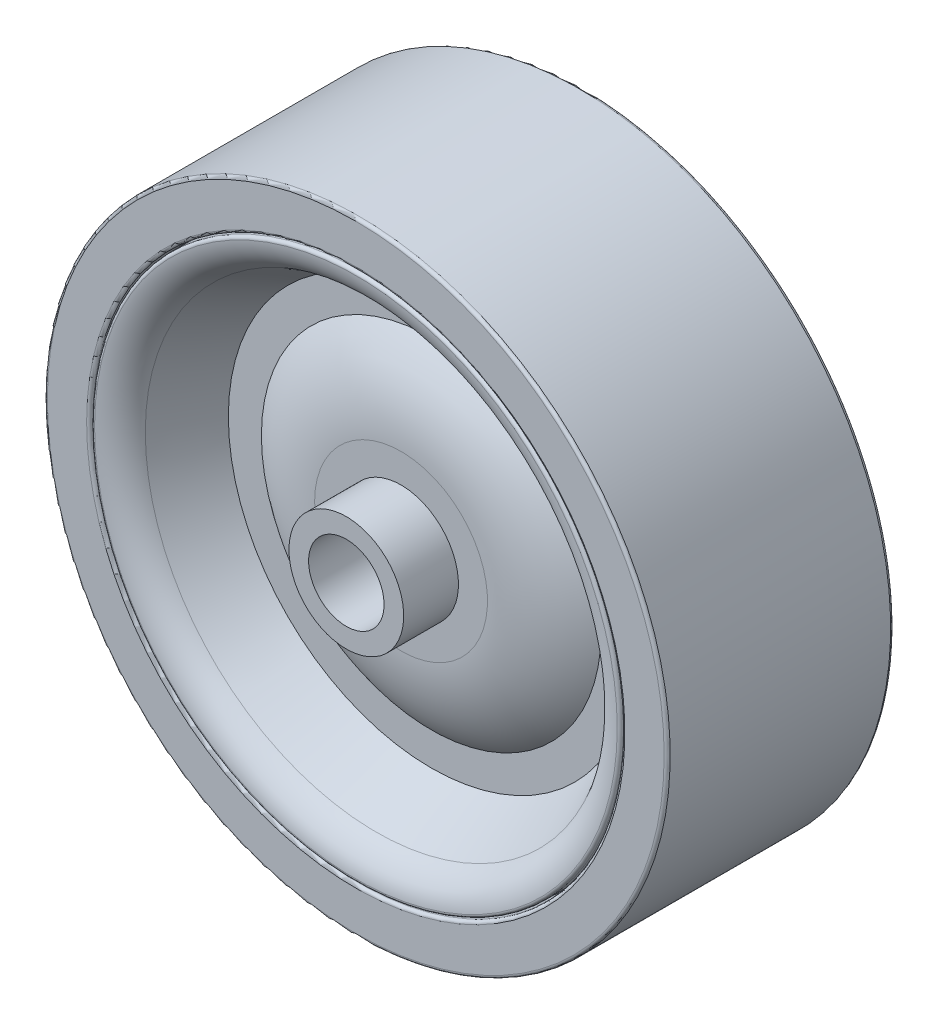
SolidWorks part; units mm, degrees
ref_plane "Front" through (0, 0, 0) normal (0, 0, 1) x (1, 0, 0)
ref_plane "Top" through (0, 0, 0) normal (0, 1, 0) x (1, 0, 0)
ref_plane "Right" through (0, 0, 0) normal (1, 0, 0) x (0, 0, -1)
sketch "Sketch1" plane through (0, 0, 0) normal (1, 0, 0) x (0, 0, -1)
  line L0 (0, 26.1937) -> (9.525, 26.1937)
  line L1 (0, 26.1937) -> (0, 3.175)
  line L2 (0, 3.175) -> (10.3188, 3.175)
  line L3 (10.3188, 3.175) -> (10.3187, 4.826)
  line L4 (10.3187, 4.826) -> (5.715, 4.826)
  line L5 (10.3187, 4.826) -> (10.3188, -4.826) construction
  line L6 (10.3188, 3.175) -> (10.3188, -3.175) construction
  line L7 (3.175, 17.0656) -> (7.7963, 19.4303)
  line L8 (0, 26.1937) -> (0, -26.1937) construction
  line L9 (10.3187, 0) -> (-10.3187, 0) construction
  line L10 (9.525, 26.1937) -> (-9.525, 26.1937) construction
  line L11 (5.715, 7.2695) -> (5.715, 4.826)
  line L12 (3.175, 14.2875) -> (3.175, 17.0656)
  line L13 (9.525, 26.1937) -> (9.525, 22.3837)
  line L14 (9.525, 22.3837) -> (6.985, 22.3837)
  line L15 (6.985, 22.3837) -> (6.985, 22.2568)
  line L16 (6.985, 22.2568) -> (9.525, 22.2568)
  line L19 (5.715, 4.826) -> (-5.715, 4.826) construction
  line L20 (3.175, 15.6766) -> (-3.175, 15.6766) construction
  arc A0 (9.525, 22.2568) -> (7.7963, 19.4303) centre (6.35, 22.2568) cw
  arc A2 (3.175, 14.2875) -> (5.715, 7.2695) centre (-5.2505, 7.2695) cw
  point P27 (0, 4.826)
  point P31 (0, 15.6766)
  dimension "D2" = 3.81
  dimension "D8" = 3.175
  dimension "D1" = 9.652
  dimension "D3" = 11.43
  dimension "D4" = 6.35
  dimension "D5" = 14.2875
  dimension "D6" = 2.7781
  dimension "D7" = 2.4435
  dimension "Bore Dia" = 6.35
  dimension "Hub Lg" = 20.6375
  dimension "Wheel Wd" = 19.05
  dimension "Wheel Dia" = 52.3875
  dimension "D9" = 0.127
  dimension "D10" = 2.54
revolve "Revolve1" add sketch "Sketch1" angle 360 about L9
fillet "Fillet1" radius 0.254 3 edges at (-26.1937, 0, -9.525) (-22.3837, 0, -9.525) (-22.2567, 0, -9.525)
mirror "Mirror1" about plane through (0, 0, 0) normal (0, 0, 1) of bodies 109
equation "\"D1@Sketch1\" = \"Bore Dia@Sketch1\" * 1.52"
